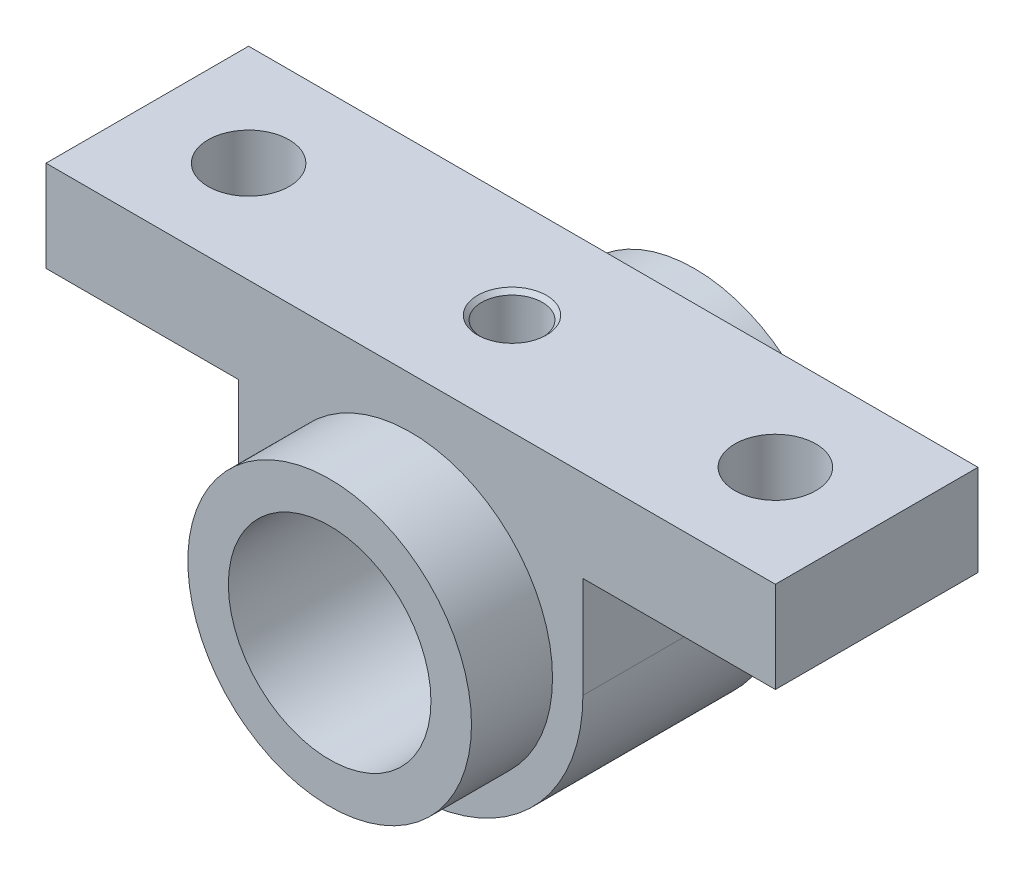
SolidWorks part; units mm, degrees
ref_plane "Front Plane" through (0, 0, 0) normal (0, 0, 1) x (1, 0, 0)
ref_plane "Top Plane" through (0, 0, 0) normal (0, 1, 0) x (1, 0, 0)
ref_plane "Right Plane" through (0, 0, 0) normal (1, 0, 0) x (0, 0, -1)
sketch "Sketch1" plane through (0, 0, 0) normal (0, 0, 1) x (1, 0, 0)
  line L0 (0, -4.5) -> (9.5, -4.5)
  line L1 (0, 0) -> (36, 0)
  line L2 (0, 0) -> (0, -4.5)
  line L4 (36, 0) -> (36, -4.5)
  line L5 (9.5, -4.5) -> (9.5, -9.5)
  line L7 (26.5, -9.5) -> (26.5, -4.5)
  line L8 (26.5, -4.5) -> (36, -4.5)
  arc A0 (9.5, -9.5) -> (26.5, -9.5) centre (18, -9.5) ccw
  circle A1 centre (18, -9.5) radius 5
  dimension "D1" = 36
  dimension "D4" = 8.5
  dimension "D8" = 10
  dimension "D2" = 9.5
  dimension "D3" = 9.5
  dimension "D5" = 5
  dimension "D6" = 4.5
  dimension "D7" = 4.5
extrude "Boss-Extrude1" add sketch "Sketch1" along normal blind 10
sketch "Sketch2" plane through (0, 0, 10) normal (0, 0, 1) x (1, 0, 0)
  circle A0 centre (18, -9.5) radius 7
  circle A1 centre (18, -9.5) radius 5
  dimension "D1" = 14
extrude "Boss-Extrude2" add sketch "Sketch2" along normal blind 4
sketch "Sketch3" plane through (0, 0, 0) normal (0, 0, -1) x (-1, 0, 0)
  circle A0 centre (-18, -9.5) radius 5
  circle A1 centre (-18, -9.5) radius 7
  dimension "D1" = 14
extrude "Boss-Extrude3" add sketch "Sketch3" along normal blind 4
sketch "Sketch4" plane through (0, 0, 0) normal (0, 1, 0) x (1, 0, 0)
  line L0 (0, -10) -> (0, 0) construction
  line L2 (36, 0) -> (0, 0) construction
  circle A0 centre (18, -5) radius 1.5
  circle A1 centre (5, -5) radius 2
  circle A2 centre (31, -5) radius 2
  point P8 (0, -5)
  point P11 (0, 0)
  point P12 (18, 0)
  dimension "D1" = 4
  dimension "D2" = 4
  dimension "D3" = 3
  dimension "D4" = 26
  dimension "D5" = 13
extrude "Cut-Extrude1" cut sketch "Sketch4" against normal blind 7
chamfer "Chamfer1" distance 0.2 angle 45 1 edges at (18, 0, 6.5)
